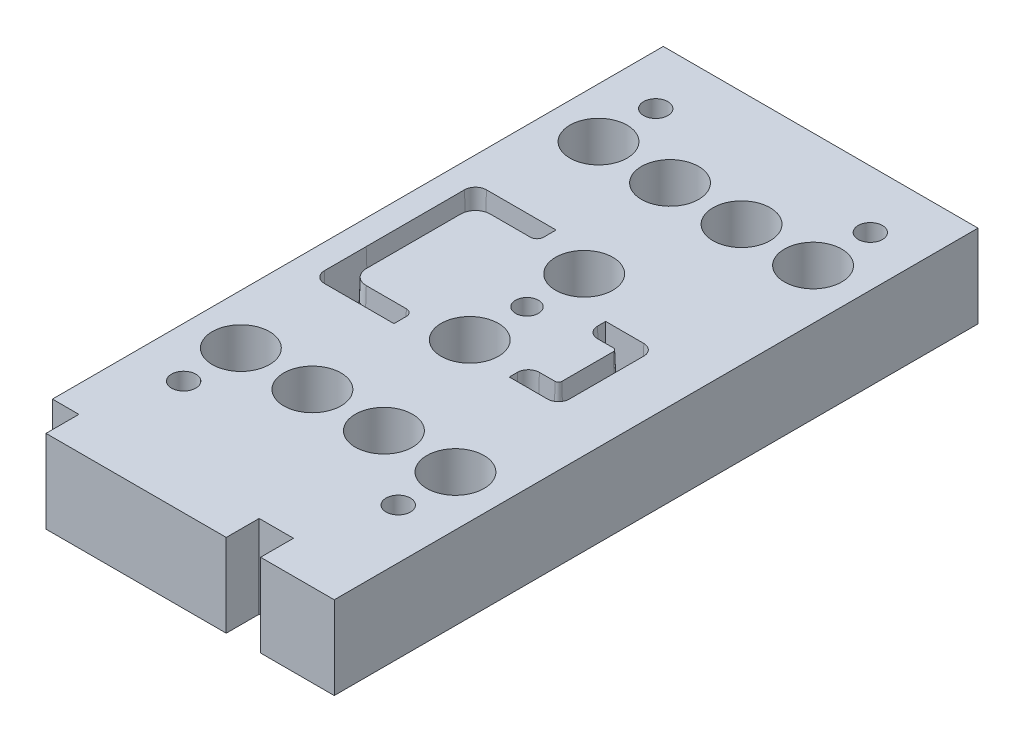
SolidWorks part; units mm, degrees
material "Plain Carbon Steel"
ref_plane "Front Plane" through (0, 0, 0) normal (0, 0, 1) x (1, 0, 0)
ref_plane "Top Plane" through (0, 0, 0) normal (0, 1, 0) x (1, 0, 0)
ref_plane "Right Plane" through (0, 0, 0) normal (1, 0, 0) x (0, 0, -1)
sketch "Sketch1" plane through (0, 0, 0) normal (0, 1, 0) x (1, 0, 0)
  line L1 (-55, -112.5) -> (55, -112.5)
  line L2 (-55, -112.5) -> (-55, 112.5)
  line L3 (-55, 112.5) -> (55, 112.5)
  line L4 (55, -112.5) -> (55, 112.5)
  line L5 (-55, -112.5) -> (55, 112.5) construction
  line L6 (-55, 112.5) -> (55, -112.5) construction
  point P0 (0, 0)
  dimension "D1" = 110
  dimension "D2" = 225
extrude "Boss-Extrude1" add sketch "Sketch1" against normal blind 29
sketch "Sketch2" plane through (0, 0, 0) normal (0, 1, 0) x (1, 0, 0)
  line L0 (-19, 37.36) -> (-19, 33.86) construction
  line L1 (-42.5, 37.36) -> (-19, 37.36) construction
  line L2 (-45.5, 34.36) -> (-45.5, -14.64) construction
  line L3 (-42.5, -17.64) -> (-19, -17.64) construction
  line L4 (-19, -17.64) -> (-19, -14.14) construction
  line L5 (-34.5, -12.64) -> (-20.5, -12.64) construction
  line L6 (-40.5, 26.36) -> (-40.5, -6.64) construction
  line L7 (-20.5, 32.36) -> (-34.5, 32.36) construction
  line L8 (-19, 37.36) -> (-19, 33.86)
  line L9 (-42.5, 37.36) -> (-19, 37.36)
  line L10 (-45.5, 34.36) -> (-45.5, -14.64)
  line L11 (-42.5, -17.64) -> (-19, -17.64)
  line L12 (-19, -17.64) -> (-19, -14.14)
  line L13 (-34.5, -12.64) -> (-20.5, -12.64)
  line L14 (-40.5, 26.36) -> (-40.5, -6.64)
  line L15 (-20.5, 32.36) -> (-34.5, 32.36)
  arc A0 (-20.5, 32.36) -> (-19, 33.86) centre (-20.5, 33.86) ccw construction
  arc A1 (-42.5, 37.36) -> (-45.5, 34.36) centre (-42.5, 34.36) ccw construction
  arc A2 (-45.5, -14.64) -> (-42.5, -17.64) centre (-42.5, -14.64) ccw construction
  arc A3 (-19, -14.14) -> (-20.5, -12.64) centre (-20.5, -14.14) ccw construction
  arc A4 (-40.5, -6.64) -> (-34.5, -12.64) centre (-34.5, -6.64) ccw construction
  arc A5 (-34.5, 32.36) -> (-40.5, 26.36) centre (-34.5, 26.36) ccw construction
  arc A6 (-20.5, 32.36) -> (-19, 33.86) centre (-20.5, 33.86) ccw
  arc A7 (-42.5, 37.36) -> (-45.5, 34.36) centre (-42.5, 34.36) ccw
  arc A8 (-45.5, -14.64) -> (-42.5, -17.64) centre (-42.5, -14.64) ccw
  arc A9 (-19, -14.14) -> (-20.5, -12.64) centre (-20.5, -14.14) ccw
  arc A10 (-40.5, -6.64) -> (-34.5, -12.64) centre (-34.5, -6.64) ccw
  arc A11 (-34.5, 32.36) -> (-40.5, 26.36) centre (-34.5, 26.36) ccw
extrude "Cut-Extrude1" cut sketch "Sketch2" against normal up to next
sketch "Sketch3" plane through (0, 0, 0) normal (0, 1, 0) x (1, 0, 0)
  line L0 (19, 18.36) -> (31.5, 18.36) construction
  line L1 (19, 18.36) -> (19, 16.36) construction
  line L2 (27.5, 13.36) -> (22, 13.36) construction
  line L3 (29.5, -6.64) -> (29.5, 11.36) construction
  line L4 (22, -8.64) -> (27.5, -8.64) construction
  line L5 (19, -13.64) -> (19, -11.64) construction
  line L6 (31.5, -13.64) -> (19, -13.64) construction
  line L7 (34.5, 15.36) -> (34.5, -10.64) construction
  line L8 (19, 18.36) -> (31.5, 18.36)
  line L9 (19, 18.36) -> (19, 16.36)
  line L10 (27.5, 13.36) -> (22, 13.36)
  line L11 (29.5, -6.64) -> (29.5, 11.36)
  line L12 (22, -8.64) -> (27.5, -8.64)
  line L13 (19, -13.64) -> (19, -11.64)
  line L14 (31.5, -13.64) -> (19, -13.64)
  line L15 (34.5, 15.36) -> (34.5, -10.64)
  arc A0 (34.5, 15.36) -> (31.5, 18.36) centre (31.5, 15.36) ccw construction
  arc A1 (19, 16.36) -> (22, 13.36) centre (22, 16.36) ccw construction
  arc A2 (29.5, 11.36) -> (27.5, 13.36) centre (27.5, 11.36) ccw construction
  arc A3 (27.5, -8.64) -> (29.5, -6.64) centre (27.5, -6.64) ccw construction
  arc A4 (22, -8.64) -> (19, -11.64) centre (22, -11.64) ccw construction
  arc A5 (31.5, -13.64) -> (34.5, -10.64) centre (31.5, -10.64) ccw construction
  arc A6 (34.5, 15.36) -> (31.5, 18.36) centre (31.5, 15.36) ccw
  arc A7 (19, 16.36) -> (22, 13.36) centre (22, 16.36) ccw
  arc A8 (29.5, 11.36) -> (27.5, 13.36) centre (27.5, 11.36) ccw
  arc A9 (27.5, -8.64) -> (29.5, -6.64) centre (27.5, -6.64) ccw
  arc A10 (22, -8.64) -> (19, -11.64) centre (22, -11.64) ccw
  arc A11 (31.5, -13.64) -> (34.5, -10.64) centre (31.5, -10.64) ccw
extrude "Cut-Extrude2" cut sketch "Sketch3" against normal up to next
sketch "Sketch4" plane through (0, -29, 0) normal (0, -1, 0) x (1, 0, 0)
  circle A0 centre (0, 100) radius 8.5
  circle A1 centre (0, -100) radius 8.5
  dimension "D1" = 17
extrude "Cut-Extrude3" cut sketch "Sketch4" against normal blind 5
sketch "Sketch5" plane through (0, 0, 0) normal (0, 1, 0) x (1, 0, 0)
  line L2 (-55, 112.5) -> (-55, -112.5) construction
  line L5 (-19, 37.36) -> (-42.5, 37.36) construction
  line L6 (-40.5, 9.86) -> (29.5, 9.86) construction
  line L7 (-40.5, -6.64) -> (-40.5, 26.36) construction
  line L9 (29.5, 11.36) -> (29.5, -6.64) construction
  circle A0 centre (-37.5, 72.36) radius 10
  circle A1 centre (-12.5, 72.36) radius 10
  circle A2 centre (12.5, 72.36) radius 10
  circle A3 centre (37.5, 72.36) radius 10
  circle A4 centre (37.5, -52.64) radius 10
  circle A5 centre (12.5, -52.64) radius 10
  circle A6 centre (-12.5, -52.64) radius 10
  circle A7 centre (-37.5, -52.64) radius 10
  circle A8 centre (0, 29.86) radius 10
  circle A9 centre (0, -10.14) radius 10
  dimension "D1" = 20
  dimension "D2" = 17.5
  dimension "D3" = 35
  dimension "D5" = 25
  dimension "D6" = 20
  dimension "D7" = 20
  dimension "D4" = 4
extrude "Cut-Extrude4" cut sketch "Sketch5" against normal blind 20
sketch "Sketch6" plane through (0, 0, 0) normal (0, 1, 0) x (1, 0, 0)
  line L0 (-55, -112.5) -> (55, -112.5) construction
  line L1 (29.25, -112.5) -> (17.25, -112.5)
  line L2 (29.25, -112.5) -> (29.25, -101)
  line L3 (29.25, -101) -> (17.25, -101)
  line L4 (17.25, -112.5) -> (17.25, -101)
  line L5 (18.75, -102) -> (27.75, -102) construction
  line L6 (-45.75, -112.5) -> (-57.75, -112.5)
  line L7 (-45.75, -112.5) -> (-45.75, -101)
  line L8 (-45.75, -101) -> (-57.75, -101)
  line L9 (-57.75, -112.5) -> (-57.75, -101)
  line L10 (28.25, -102.5) -> (28.25, -115) construction
  line L11 (18.25, -115) -> (18.25, -102.5) construction
  line L12 (-56.75, -115) -> (-56.75, -102.5) construction
  line L13 (-46.75, -102.5) -> (-46.75, -115) construction
  line L14 (-56.25, -102) -> (-47.25, -102) construction
  dimension "D1" = 1
  dimension "D2" = 1
  dimension "D3" = 1
  dimension "D4" = 1
  dimension "D5" = 1
  dimension "D6" = 1
extrude "Cut-Extrude5" cut sketch "Sketch6" against normal up to next
hole_wizard "M10 Tapped Hole1" positions "Sketch9" profile "Sketch8" tap size "M10" standard "ISO" end condition through all
sketch "Sketch9" plane through (0, 0, 0) normal (0, 1, 0) x (1, 0, 0)
  line L2 (-37.5, 72.36) -> (-37.5, 92.36) construction
  line L4 (37.5, 72.36) -> (37.5, 92.36) construction
  circle A1 centre (-37.5, 72.36) radius 10 construction
  circle A2 centre (-37.5, -52.64) radius 10 construction
  point P0 (-37.5, -72.64)
  point P2 (37.5, -72.64)
  point P4 (37.5, 92.36)
  point P6 (-37.5, 92.36)
  dimension "D1" = 20
  dimension "D2" = 20
sketch "Sketch8" plane through (-37.5, 0, 72.64) normal (1, 0, 0) x (0, 0, 1)
  line L0 (0, 0) -> (0, 29)
  line L1 (0, 29) -> (4.25, 29)
  line L2 (4.25, 29) -> (4.25, 0)
  line L5 (4.25, 0) -> (0, 0)
  line L11 (0, -6.35) -> (0, 107.95) construction
  dimension "Thru Tap Drill Dia." = 8.5
  dimension "Thru Tap Drill Depth" = 29
cosmetic thread "Hole Thread1" parameters "D2"=10
cosmetic thread "Hole Thread2" parameters "D2"=10
cosmetic thread "Hole Thread3" parameters "D2"=10
cosmetic thread "Hole Thread4" parameters "D2"=10
sketch "Sketch10" plane through (0, 0, 0) normal (0, 1, 0) x (1, 0, 0)
  circle A0 centre (0, 9.86) radius 5 construction
  circle A1 centre (0, 9.86) radius 5 construction
  circle A2 centre (0, 9.86) radius 4
  dimension "D1" = 8
extrude "Cut-Extrude6" cut sketch "Sketch10" against normal up to next
sketch "Sketch11" plane through (0, 0, 0) normal (0, 0, 1) x (1, 0, 0)
  line L0 (-45.5, -24) -> (-45.5, 0)
  line L1 (-45.5, -29) -> (-45.5, 0) construction
  line L2 (60.5, 0) -> (-60.5, 0) construction
  line L3 (-45.5, 0) -> (-46.3381, 0)
  line L4 (-46.3381, 0) -> (-45.5, -24)
  line L5 (55, -29) -> (-55, -29) construction
  dimension "D1" = 5
  dimension "D2" = 2
sketch "Sketch12" plane through (0, 0, 0) normal (0, 1, 0) x (1, 0, 0)
  line L0 (-19, 33.86) -> (-19, 37.36) construction
  line L1 (-34.5, 32.36) -> (-20.5, 32.36) construction
  line L2 (-40.5, -6.64) -> (-40.5, 26.36) construction
  line L3 (-19, -17.64) -> (-19, -14.14) construction
  line L4 (-20.5, -12.64) -> (-34.5, -12.64) construction
  line L5 (-19, 33.86) -> (-19, 37.36)
  line L6 (-34.5, 32.36) -> (-20.5, 32.36)
  line L7 (-40.5, -6.64) -> (-40.5, 26.36)
  line L8 (-19, -17.64) -> (-19, -14.14)
  line L9 (-20.5, -12.64) -> (-34.5, -12.64)
  line L10 (-19, 37.36) -> (-42.5, 37.36) construction
  line L11 (-45.5, 34.36) -> (-45.5, -14.64) construction
  line L12 (-42.5, -17.64) -> (-19, -17.64) construction
  line L13 (-19, 37.36) -> (-42.5, 37.36)
  line L14 (-45.5, 34.36) -> (-45.5, -14.64)
  line L15 (-42.5, -17.64) -> (-19, -17.64)
  arc A0 (-20.5, 32.36) -> (-19, 33.86) centre (-20.5, 33.86) ccw construction
  arc A1 (-34.5, 32.36) -> (-40.5, 26.36) centre (-34.5, 26.36) ccw construction
  arc A2 (-40.5, -6.64) -> (-34.5, -12.64) centre (-34.5, -6.64) ccw construction
  arc A3 (-19, -14.14) -> (-20.5, -12.64) centre (-20.5, -14.14) ccw construction
  arc A4 (-20.5, 32.36) -> (-19, 33.86) centre (-20.5, 33.86) ccw
  arc A5 (-34.5, 32.36) -> (-40.5, 26.36) centre (-34.5, 26.36) ccw
  arc A6 (-40.5, -6.64) -> (-34.5, -12.64) centre (-34.5, -6.64) ccw
  arc A7 (-19, -14.14) -> (-20.5, -12.64) centre (-20.5, -14.14) ccw
  arc A8 (-42.5, 37.36) -> (-45.5, 34.36) centre (-42.5, 34.36) ccw construction
  arc A9 (-45.5, -14.64) -> (-42.5, -17.64) centre (-42.5, -14.64) ccw construction
  arc A10 (-42.5, 37.36) -> (-45.5, 34.36) centre (-42.5, 34.36) ccw
  arc A11 (-45.5, -14.64) -> (-42.5, -17.64) centre (-42.5, -14.64) ccw
sweep "Cut-Sweep1" cut profiles "Sketch11" path "Sketch12"
sketch "Sketch13" plane through (0, 0, 0) normal (0, 0, 1) x (1, 0, 0)
  line L0 (34.5, -24) -> (34.5, 0)
  line L1 (34.5, -29) -> (34.5, 0) construction
  line L2 (34.5, 0) -> (35.3381, 0)
  line L3 (60.5, 0) -> (-60.5, 0) construction
  line L4 (35.3381, 0) -> (34.5, -24)
  line L5 (55, -29) -> (-55, -29) construction
  dimension "D1" = 5
  dimension "D2" = 2
sketch "Sketch14" plane through (0, 0, 0) normal (0, 1, 0) x (1, 0, 0)
  line L0 (19, -11.64) -> (19, -13.64) construction
  line L1 (27.5, -8.64) -> (22, -8.64) construction
  line L2 (19, 18.36) -> (19, 16.36) construction
  line L3 (22, 13.36) -> (27.5, 13.36) construction
  line L4 (29.5, 11.36) -> (29.5, -6.64) construction
  line L5 (19, -11.64) -> (19, -13.64)
  line L6 (27.5, -8.64) -> (22, -8.64)
  line L7 (19, 18.36) -> (19, 16.36)
  line L8 (22, 13.36) -> (27.5, 13.36)
  line L9 (29.5, 11.36) -> (29.5, -6.64)
  line L10 (31.5, 18.36) -> (19, 18.36) construction
  line L11 (34.5, -10.64) -> (34.5, 15.36) construction
  line L12 (19, -13.64) -> (31.5, -13.64) construction
  line L13 (31.5, 18.36) -> (19, 18.36)
  line L14 (34.5, -10.64) -> (34.5, 15.36)
  line L15 (19, -13.64) -> (31.5, -13.64)
  arc A0 (22, -8.64) -> (19, -11.64) centre (22, -11.64) ccw construction
  arc A1 (27.5, -8.64) -> (29.5, -6.64) centre (27.5, -6.64) ccw construction
  arc A2 (19, 16.36) -> (22, 13.36) centre (22, 16.36) ccw construction
  arc A3 (29.5, 11.36) -> (27.5, 13.36) centre (27.5, 11.36) ccw construction
  arc A4 (22, -8.64) -> (19, -11.64) centre (22, -11.64) ccw
  arc A5 (27.5, -8.64) -> (29.5, -6.64) centre (27.5, -6.64) ccw
  arc A6 (19, 16.36) -> (22, 13.36) centre (22, 16.36) ccw
  arc A7 (29.5, 11.36) -> (27.5, 13.36) centre (27.5, 11.36) ccw
  arc A8 (34.5, 15.36) -> (31.5, 18.36) centre (31.5, 15.36) ccw construction
  arc A9 (31.5, -13.64) -> (34.5, -10.64) centre (31.5, -10.64) ccw construction
  arc A10 (34.5, 15.36) -> (31.5, 18.36) centre (31.5, 15.36) ccw
  arc A11 (31.5, -13.64) -> (34.5, -10.64) centre (31.5, -10.64) ccw
sweep "Cut-Sweep2" cut profiles "Sketch13" path "Sketch14"
